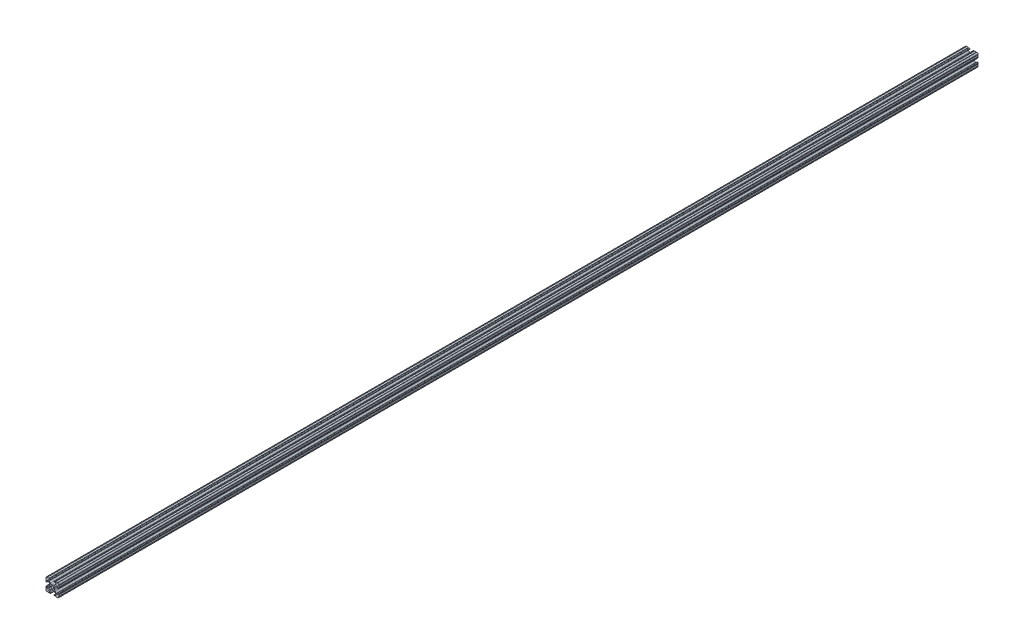
SolidWorks part; units mm, degrees
ref_plane "Front Plane" through (0, 0, 0) normal (0, 0, 1) x (1, 0, 0)
ref_plane "Top Plane" through (0, 0, 0) normal (0, 1, 0) x (1, 0, 0)
ref_plane "Right Plane" through (0, 0, 0) normal (1, 0, 0) x (0, 0, -1)
sketch "Sketch1" plane through (0, 0, 0) normal (0, 0, 1) x (1, 0, 0)
  line L88 (-7.1797, -8.6452) -> (-3.9523, -5.4237)
  line L89 (-1.7093, -4.4958) -> (1.7093, -4.4958)
  line L90 (3.9523, -5.4237) -> (7.1797, -8.6452)
  line L91 (6.4164, -10.4902) -> (4.2875, -10.4902)
  line L92 (3.2385, -11.5392) -> (3.2385, -11.651)
  line L93 (4.2875, -12.7) -> (5.3171, -12.7)
  line L94 (6.3331, -12.7) -> (9.5504, -12.7)
  line L95 (12.7, -9.5504) -> (12.7, -6.3331)
  line L96 (12.7, -5.3171) -> (12.7, -4.2875)
  line L97 (11.651, -3.2385) -> (11.5392, -3.2385)
  line L98 (10.4902, -4.2875) -> (10.4902, -6.4021)
  line L99 (8.7371, -7.1294) -> (5.441, -3.8408)
  line L100 (4.5085, -1.5932) -> (4.5085, 1.5932)
  line L101 (5.441, 3.8408) -> (8.7371, 7.1294)
  line L102 (10.4902, 6.4021) -> (10.4902, 4.2875)
  line L103 (11.5392, 3.2385) -> (11.651, 3.2385)
  line L104 (12.7, 4.2875) -> (12.7, 5.3171)
  line L105 (12.7, 6.3331) -> (12.7, 9.5504)
  line L106 (9.5504, 12.7) -> (6.3331, 12.7)
  line L107 (5.3171, 12.7) -> (4.2875, 12.7)
  line L108 (3.2385, 11.651) -> (3.2385, 11.5392)
  line L109 (4.2875, 10.4902) -> (6.4768, 10.4902)
  line L110 (7.207, 8.7244) -> (3.8983, 5.4232)
  line L111 (1.6558, 4.4958) -> (-1.6558, 4.4958)
  line L112 (-3.8983, 5.4232) -> (-7.207, 8.7244)
  line L113 (-6.4768, 10.4902) -> (-4.2875, 10.4902)
  line L114 (-3.2385, 11.5392) -> (-3.2385, 11.651)
  line L115 (-4.2875, 12.7) -> (-5.3171, 12.7)
  line L116 (-6.3331, 12.7) -> (-9.5504, 12.7)
  line L117 (-12.7, 9.5504) -> (-12.7, 6.3331)
  line L118 (-12.7, 5.3171) -> (-12.7, 4.2875)
  line L119 (-11.651, 3.2385) -> (-11.5392, 3.2385)
  line L120 (-10.4902, 4.2875) -> (-10.4902, 6.4021)
  line L121 (-8.7371, 7.1294) -> (-5.441, 3.8408)
  line L122 (-4.5085, 1.5932) -> (-4.5085, -1.5932)
  line L123 (-5.441, -3.8408) -> (-8.7371, -7.1294)
  line L124 (-10.4902, -6.4021) -> (-10.4902, -4.2875)
  line L125 (-11.5392, -3.2385) -> (-11.651, -3.2385)
  line L126 (-12.7, -4.2875) -> (-12.7, -5.3171)
  line L127 (-12.7, -6.3331) -> (-12.7, -9.5504)
  line L128 (-9.5504, -12.7) -> (-6.3331, -12.7)
  line L129 (-5.3171, -12.7) -> (-4.2875, -12.7)
  line L130 (-3.2385, -11.651) -> (-3.2385, -11.5392)
  line L131 (-4.2875, -10.4902) -> (-6.4164, -10.4902)
  circle A1 centre (0, 0) radius 2.6035
  arc A104 (-7.1797, -8.6452) -> (-6.4164, -10.4902) centre (-6.4164, -9.4098) ccw
  arc A105 (-1.7093, -4.4958) -> (-3.9523, -5.4237) centre (-1.7093, -7.6708) ccw
  arc A106 (3.9523, -5.4237) -> (1.7093, -4.4958) centre (1.7093, -7.6708) ccw
  arc A107 (6.4164, -10.4902) -> (7.1797, -8.6452) centre (6.4164, -9.4098) ccw
  arc A108 (4.2875, -10.4902) -> (3.2385, -11.5392) centre (4.2875, -11.5392) ccw
  arc A109 (3.2385, -11.651) -> (4.2875, -12.7) centre (4.2875, -11.651) ccw
  arc A110 (6.3331, -12.7) -> (5.3171, -12.7) centre (5.8251, -12.7) ccw
  arc A111 (10.5664, -12.6998) -> (9.5504, -12.7) centre (10.0584, -12.7) ccw
  arc A112 (10.5664, -12.6998) -> (12.6998, -10.5664) centre (10.5918, -10.5918) ccw
  arc A113 (12.7, -9.5504) -> (12.6998, -10.5664) centre (12.7, -10.0584) ccw
  arc A114 (12.7, -5.3171) -> (12.7, -6.3331) centre (12.7, -5.8251) ccw
  arc A115 (12.7, -4.2875) -> (11.651, -3.2385) centre (11.651, -4.2875) ccw
  arc A116 (11.5392, -3.2385) -> (10.4902, -4.2875) centre (11.5392, -4.2875) ccw
  arc A117 (8.7371, -7.1294) -> (10.4902, -6.4021) centre (9.4628, -6.4021) ccw
  arc A118 (4.5085, -1.5932) -> (5.441, -3.8408) centre (7.6835, -1.5932) ccw
  arc A119 (5.441, 3.8408) -> (4.5085, 1.5932) centre (7.6835, 1.5932) ccw
  arc A120 (10.4902, 6.4021) -> (8.7371, 7.1294) centre (9.4628, 6.4021) ccw
  arc A121 (10.4902, 4.2875) -> (11.5392, 3.2385) centre (11.5392, 4.2875) ccw
  arc A122 (11.651, 3.2385) -> (12.7, 4.2875) centre (11.651, 4.2875) ccw
  arc A123 (12.7, 6.3331) -> (12.7, 5.3171) centre (12.7, 5.8251) ccw
  arc A124 (12.6998, 10.5664) -> (12.7, 9.5504) centre (12.7, 10.0584) ccw
  arc A125 (12.6998, 10.5664) -> (10.5664, 12.6998) centre (10.5918, 10.5918) ccw
  arc A126 (9.5504, 12.7) -> (10.5664, 12.6998) centre (10.0584, 12.7) ccw
  arc A127 (5.3171, 12.7) -> (6.3331, 12.7) centre (5.8251, 12.7) ccw
  arc A128 (4.2875, 12.7) -> (3.2385, 11.651) centre (4.2875, 11.651) ccw
  arc A129 (3.2385, 11.5392) -> (4.2875, 10.4902) centre (4.2875, 11.5392) ccw
  arc A130 (7.207, 8.7244) -> (6.4768, 10.4902) centre (6.4768, 9.4563) ccw
  arc A131 (1.6558, 4.4958) -> (3.8983, 5.4232) centre (1.6558, 7.6708) ccw
  arc A132 (-3.8983, 5.4232) -> (-1.6558, 4.4958) centre (-1.6558, 7.6708) ccw
  arc A133 (-6.4768, 10.4902) -> (-7.207, 8.7244) centre (-6.4768, 9.4563) ccw
  arc A134 (-4.2875, 10.4902) -> (-3.2385, 11.5392) centre (-4.2875, 11.5392) ccw
  arc A135 (-3.2385, 11.651) -> (-4.2875, 12.7) centre (-4.2875, 11.651) ccw
  arc A136 (-6.3331, 12.7) -> (-5.3171, 12.7) centre (-5.8251, 12.7) ccw
  arc A137 (-10.5664, 12.6998) -> (-9.5504, 12.7) centre (-10.0584, 12.7) ccw
  arc A138 (-10.5664, 12.6998) -> (-12.6998, 10.5664) centre (-10.5918, 10.5918) ccw
  arc A139 (-12.7, 9.5504) -> (-12.6998, 10.5664) centre (-12.7, 10.0584) ccw
  arc A140 (-12.7, 5.3171) -> (-12.7, 6.3331) centre (-12.7, 5.8251) ccw
  arc A141 (-12.7, 4.2875) -> (-11.651, 3.2385) centre (-11.651, 4.2875) ccw
  arc A142 (-11.5392, 3.2385) -> (-10.4902, 4.2875) centre (-11.5392, 4.2875) ccw
  arc A143 (-8.7371, 7.1294) -> (-10.4902, 6.4021) centre (-9.4628, 6.4021) ccw
  arc A144 (-4.5085, 1.5932) -> (-5.441, 3.8408) centre (-7.6835, 1.5932) ccw
  arc A145 (-5.441, -3.8408) -> (-4.5085, -1.5932) centre (-7.6835, -1.5932) ccw
  arc A146 (-10.4902, -6.4021) -> (-8.7371, -7.1294) centre (-9.4628, -6.4021) ccw
  arc A147 (-10.4902, -4.2875) -> (-11.5392, -3.2385) centre (-11.5392, -4.2875) ccw
  arc A148 (-11.651, -3.2385) -> (-12.7, -4.2875) centre (-11.651, -4.2875) ccw
  arc A149 (-12.7, -6.3331) -> (-12.7, -5.3171) centre (-12.7, -5.8251) ccw
  arc A150 (-12.6998, -10.5664) -> (-12.7, -9.5504) centre (-12.7, -10.0584) ccw
  arc A151 (-12.6998, -10.5664) -> (-10.5664, -12.6998) centre (-10.5918, -10.5918) ccw
  arc A152 (-9.5504, -12.7) -> (-10.5664, -12.6998) centre (-10.0584, -12.7) ccw
  arc A153 (-5.3171, -12.7) -> (-6.3331, -12.7) centre (-5.8251, -12.7) ccw
  arc A154 (-4.2875, -12.7) -> (-3.2385, -11.651) centre (-4.2875, -11.651) ccw
  arc A155 (-3.2385, -11.5392) -> (-4.2875, -10.4902) centre (-4.2875, -11.5392) ccw
extrude "Boss-Extrude1" add sketch "Sketch1" along normal mid plane 1828.8
sketch "Sketch2" plane through (4.5085, 0, 0) normal (1, 0, 0) x (0, 0, -1)
  line L0 (-914.4, -1.5932) -> (-914.4, 1.5932) construction
  circle A0 centre (0, 0) radius 3.175
  circle A1 centre (76.2, 0) radius 3.175
  circle A2 centre (-76.2, 0) radius 3.175
  dimension "D1" = 6.35
  dimension "D2" = 914.4
  dimension "D3" = 6.35
  dimension "D4" = 6.35
  dimension "D5" = 76.2
  dimension "D6" = 76.2
extrude "Cut-Extrude1" cut sketch "Sketch2" against normal through all and the other way through all
